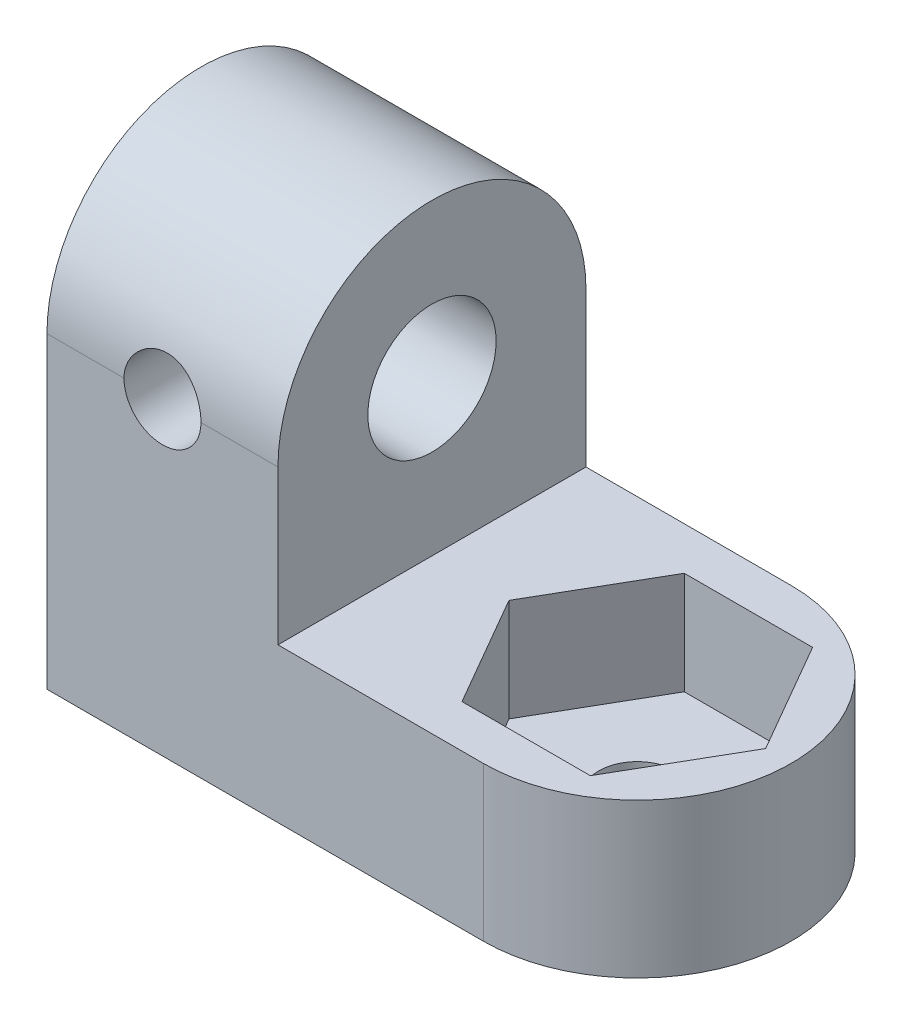
SolidWorks part; units mm, degrees
material "5052-H34"
ref_plane "前视基准面" through (0, 0, 0) normal (0, 0, 1) x (1, 0, 0)
ref_plane "上视基准面" through (0, 0, 0) normal (0, 1, 0) x (1, 0, 0)
ref_plane "右视基准面" through (0, 0, 0) normal (1, 0, 0) x (0, 0, -1)
sketch "草图1" plane through (0, 0, 0) normal (0, 1, 0) x (1, 0, 0)
  line L0 (0, 0) -> (0, 6)
  line L7 (0, 6) -> (-17, 6)
  line L8 (0, 0) -> (0, -6)
  line L9 (0, -6) -> (-17, -6)
  line L10 (-17, 6) -> (-17, -6)
  line L11 (-17, 6) -> (-6, 6)
  circle A1 centre (0, 0) radius 6
extrude "凸台-拉伸1" add sketch "草图1" along normal blind 6 contours A1 L7 L10 L9 | L0 A1 L8 | L8 A1 L0
sketch "草图2" plane through (0, 6, 0) normal (0, 1, 0) x (1, 0, 0)
  line L1 (2.5, -4.3301) -> (5, 0)
  line L2 (5, 0) -> (2.5, 4.3301)
  line L3 (2.5, 4.3301) -> (-2.5, 4.3301)
  line L4 (-2.5, 4.3301) -> (-5, 0)
  line L5 (-5, 0) -> (-2.5, -4.3301)
  line L6 (-2.5, -4.3301) -> (2.5, -4.3301)
  circle A0 centre (0, 0) radius 4.3301 construction
extrude "切除-拉伸1" cut sketch "草图2" against normal blind 4
sketch "草图3" plane through (0, 0, 0) normal (0, -1, 0) x (1, 0, 0)
  circle A0 centre (0, 0) radius 1.5
extrude "切除-拉伸2" cut sketch "草图3" against normal blind 4
sketch "草图5" plane through (0, 6, 0) normal (0, 1, 0) x (1, 0, 0)
  line L0 (-17, -6) -> (-8, -6)
  line L1 (0, -6) -> (-17, -6) construction
  line L5 (-17, 6) -> (-17, -6)
  line L6 (-8, -6) -> (-8, 6)
  line L7 (0, 6) -> (-17, 6) construction
  line L8 (-8, 6) -> (-17, 6)
extrude "凸台-拉伸2" add sketch "草图5" along normal blind 12
sketch "草图6" plane through (-17, 0, 0) normal (-1, 0, 0) x (0, 0, 1)
  line L0 (-6, 18) -> (0, 18)
  line L1 (-6, 18) -> (6, 18) construction
  line L2 (0, 18) -> (0, 12)
  line L3 (-6, 12) -> (-6, 18)
  line L4 (6, 18) -> (0, 18)
  line L5 (6, 12) -> (6, 18)
  circle A0 centre (0, 12) radius 6
  line M4 (6, 0) -> (6, 18)
  line M5 (6, 18) -> (-6, 18)
  line M6 (-6, 18) -> (-6, 0)
extrude "切除-拉伸3" cut sketch "草图6" against normal through all contours A0 M5 M6 | A0 M4 M5
sketch "草图9" plane through (-8, 0, 0) normal (1, 0, 0) x (0, 0, -1)
  circle A0 centre (0, 12) radius 2.5
extrude "切除-拉伸6" cut sketch "草图9" against normal through all
sketch "草图10" plane through (0, 0, 0) normal (0, 0, 1) x (1, 0, 0)
  line L0 (-17, 0) -> (-12.5, 0)
  line L1 (0, 0) -> (-17, 0) construction
  line L2 (-12.5, 0) -> (-12.5, 12)
  line L3 (-8, 12) -> (-17, 12) construction
  circle A0 centre (-12.5, 12) radius 1.5
extrude "切除-拉伸7" cut sketch "草图10" against normal through all both and the other way through all
